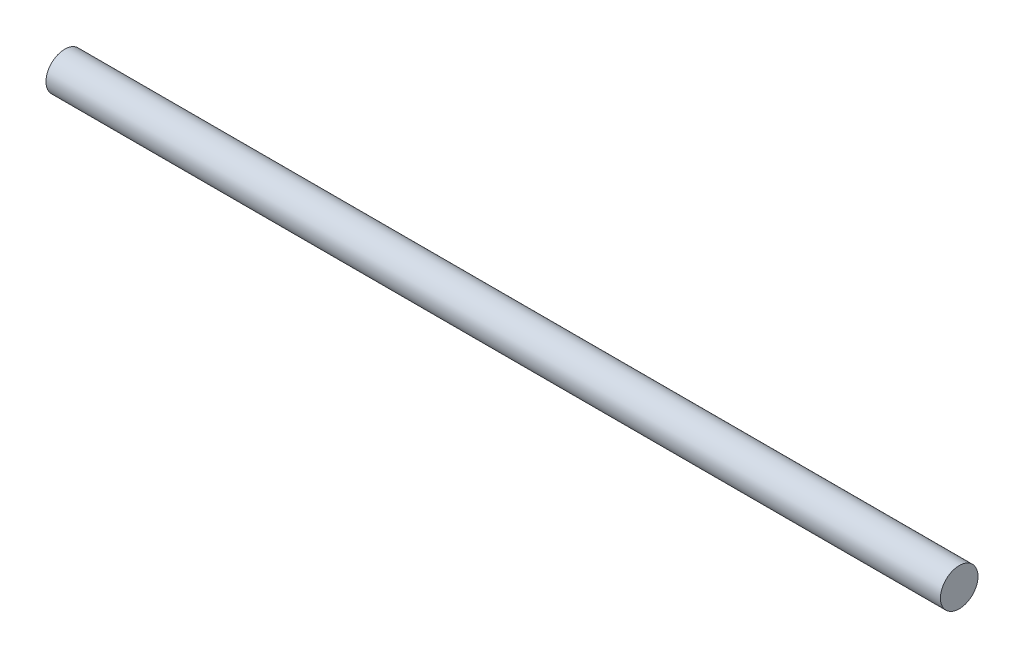
SolidWorks part; units mm, degrees
ref_plane "Front Plane" through (0, 0, 0) normal (0, 0, 1) x (1, 0, 0)
ref_plane "Top Plane" through (0, 0, 0) normal (0, 1, 0) x (1, 0, 0)
ref_plane "Right Plane" through (0, 0, 0) normal (1, 0, 0) x (0, 0, -1)
sketch "Sketch1" plane through (0, 0, 0) normal (1, 0, 0) x (0, 0, -1)
  circle A0 centre (0, 0) radius 4.2
  dimension "D1" = 8.4
extrude "Boss-Extrude1" add sketch "Sketch1" along normal mid plane 200
cosmetic thread "Cosmetic Thread1" parameters "D1"=15, "D2"=6.619
